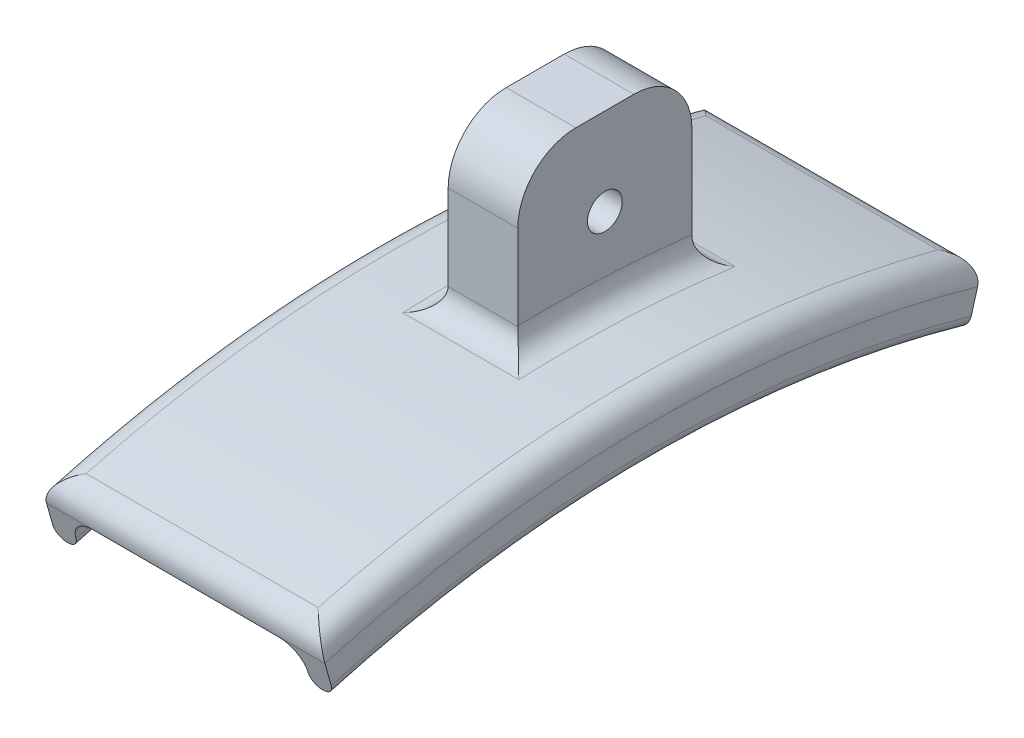
SolidWorks part; units mm, degrees
ref_plane "Alzado" through (0, 0, 0) normal (0, 0, 1) x (1, 0, 0)
ref_plane "Planta" through (0, 0, 0) normal (0, 1, 0) x (1, 0, 0)
ref_plane "Vista lateral" through (0, 0, 0) normal (1, 0, 0) x (0, 0, -1)
sketch "Croquis1" plane through (0, 0, 0) normal (1, 0, 0) x (0, 0, -1)
  line L0 (-27.3049, -3.8) -> (-28.6702, 1.01)
  line L5 (3.4941, 4.9418) -> (-58.104, -12.5418) construction
  line L6 (0, 0) -> (0, 5) construction
  line L7 (-3.4941, 4.9418) -> (58.104, -12.5418) construction
  line L8 (27.3049, -3.8) -> (28.6702, 1.01)
  circle A3 centre (0, -100) radius 100 construction
  circle A4 centre (0, -100) radius 105 construction
  arc A5 (28.6702, 1.01) -> (-28.6702, 1.01) centre (0, -100) ccw
  arc A6 (27.3049, -3.8) -> (-27.3049, -3.8) centre (0, -100) ccw
  point P2 (-27.3049, -3.8)
  point P3 (27.3049, -3.8)
  point P11 (-27.3049, -3.8)
  dimension "D1" = 200
  dimension "D2" = 3.8
  dimension "D3" = 5
extrude "Saliente-Extruir1" add sketch "Croquis1" along normal mid plane 24
sketch "Croquis7" plane through (0, 0, 0) normal (1, 0, 0) x (0, 0, -1)
  line L1 (-2.5, 4.2533) -> (12.5, 4.2533) construction
  line L2 (-2.5, 4.2533) -> (-2.5, 19.2533) construction
  line L3 (-2.5, 19.2533) -> (12.5, 19.2533) construction
  line L4 (12.5, 4.2533) -> (12.5, 19.2533) construction
  line L5 (2.5, 19.2533) -> (7.5, 19.2533)
  line L6 (12.5, 14.2533) -> (12.5, 4.2533) construction
  line L8 (-2.5, 14.2533) -> (-2.5, 4.9702)
  line L9 (12.5, 14.2533) -> (12.5, 4.2533)
  circle A2 centre (5, 11.7533) radius 1.5
  arc A3 (-2.5, 14.2533) -> (2.5, 19.2533) centre (2.5, 14.2533) cw
  arc A4 (7.5, 19.2533) -> (12.5, 14.2533) centre (7.5, 14.2533) cw
  arc A6 (28.6702, 1.01) -> (-28.6702, 1.01) centre (0, -100) ccw construction
  arc A7 (12.5, 4.2533) -> (-2.5, 4.9702) centre (0, -100) ccw
  point P8 (12.5, 11.7533)
  point P11 (5, 4.2533)
  dimension "D2" = 3
  dimension "D3" = 5
  dimension "D1" = 15
  dimension "D4" = 5
extrude "Saliente-Extruir2" add sketch "Croquis7" along normal mid plane 6
fillet "Redondeo1" radius 2 8 edges at (-3, 4.8803, -5.0128) (0, 4.9702, 2.5) (3, 4.8803, -5.0128) (0, 4.2533, -12.5) (0, 1.01, -28.6702) (12, 5, 0) (0, 1.01, 28.6702) (-12, 5, 0)
sketch "Croquis11" plane through (0, -7.4556, 26.2674) normal (0, -0.273, 0.962) x (1, 0, 0)
  line L0 (12, 6.7806) -> (-12, 6.7806) construction
  line L1 (-8, 6.7806) -> (8, 6.7806)
  line L2 (-10, 4.7806) -> (-10, 3.8)
  line L3 (-10, 3.8) -> (10, 3.8)
  line L4 (10, 4.7806) -> (10, 3.8)
  line L5 (12, 3.8) -> (-12, 3.8) construction
  arc A0 (8, 6.7806) -> (10, 4.7806) centre (8, 4.7806) cw
  arc A1 (-8, 6.7806) -> (-10, 4.7806) centre (-8, 4.7806) ccw
  point P8 (0, 6.7806)
  point P14 (-10, 6.7806)
  dimension "D2" = 2
  dimension "D1" = 20
revolve "Cortar-Revolución1" cut sketch "Croquis11" angle 360 about axis through (12, -100, 0) along (-1, 0, 0)
fillet "Redondeo2" radius 1 2 edges at (-10, 0, 0) (10, 0, 0)
fillet "Redondeo3" radius 1 2 edges at (12, 0, 0) (-12, 0, 0)
